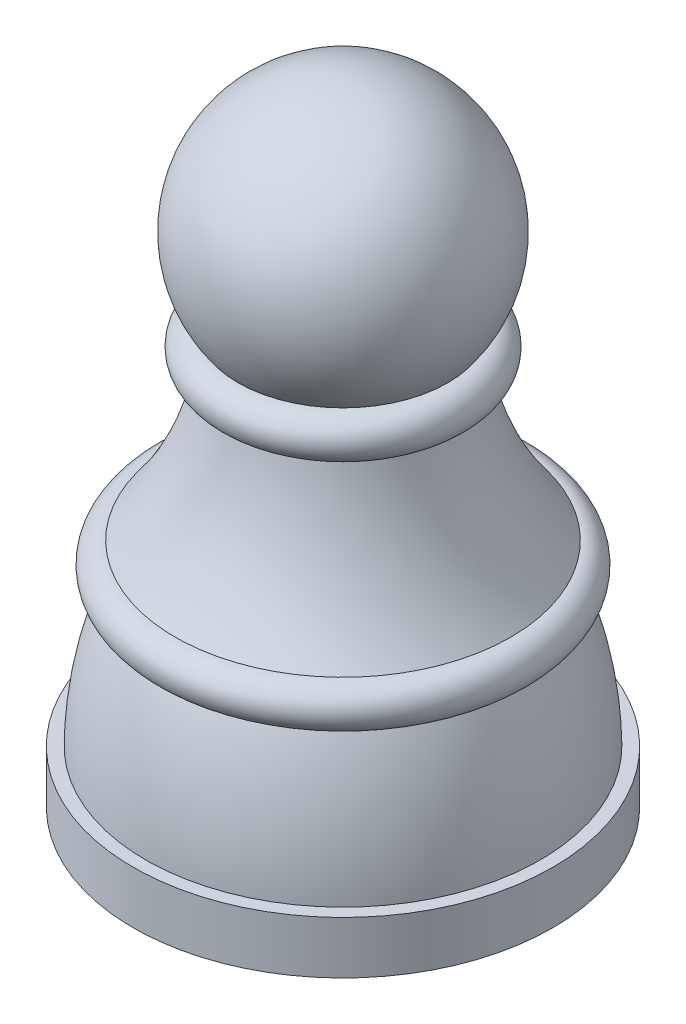
SolidWorks part; units mm, degrees
ref_plane "Front Plane" through (0, 0, 0) normal (0, 0, 1) x (1, 0, 0)
ref_plane "Top Plane" through (0, 0, 0) normal (0, 1, 0) x (1, 0, 0)
ref_plane "Right Plane" through (0, 0, 0) normal (1, 0, 0) x (0, 0, -1)
sketch "Sketch1" plane through (0, 0, 0) normal (0, 0, 1) x (1, 0, 0)
  line L0 (0, 0) -> (12.7, 0)
  line L1 (12.7, 0) -> (12.7, 3.175)
  line L2 (12.7, 3.175) -> (11.938, 3.175)
  line L3 (0, 38.1) -> (0, 0)
  line L4 (10.16, 13.97) -> (10.16, 11.43) construction
  line L5 (6.35, 25.4) -> (6.35, 22.86) construction
  arc A0 (11.938, 3.175) -> (10.16, 11.43) centre (-9.432, 2.8912) ccw
  arc A1 (10.16, 11.43) -> (10.16, 13.97) centre (10.16, 12.7) ccw
  arc A3 (6.35, 22.86) -> (6.35, 25.4) centre (6.35, 24.13) ccw
  arc A4 (6.35, 25.4) -> (0, 38.1) centre (0, 30.1625) ccw
  arc A5 (6.35, 22.86) -> (10.16, 13.97) centre (25.7891, 25.9296) ccw
  dimension "D3" = 7.9375
  dimension "D10" = 1.27
  dimension "D12" = 1.27
  dimension "D13" = 21.3719
  dimension "D14" = 19.68
  dimension "D1" = 12.7
  dimension "D2" = 12.7
  dimension "D4" = 6.35
  dimension "D5" = 6.35
  dimension "D6" = 3.175
  dimension "D7" = 12.7
  dimension "D8" = 38.1
  dimension "D9" = 10.16
  dimension "D11" = 0.762
revolve "Revolve1" add sketch "Sketch1" angle 360 about L3
